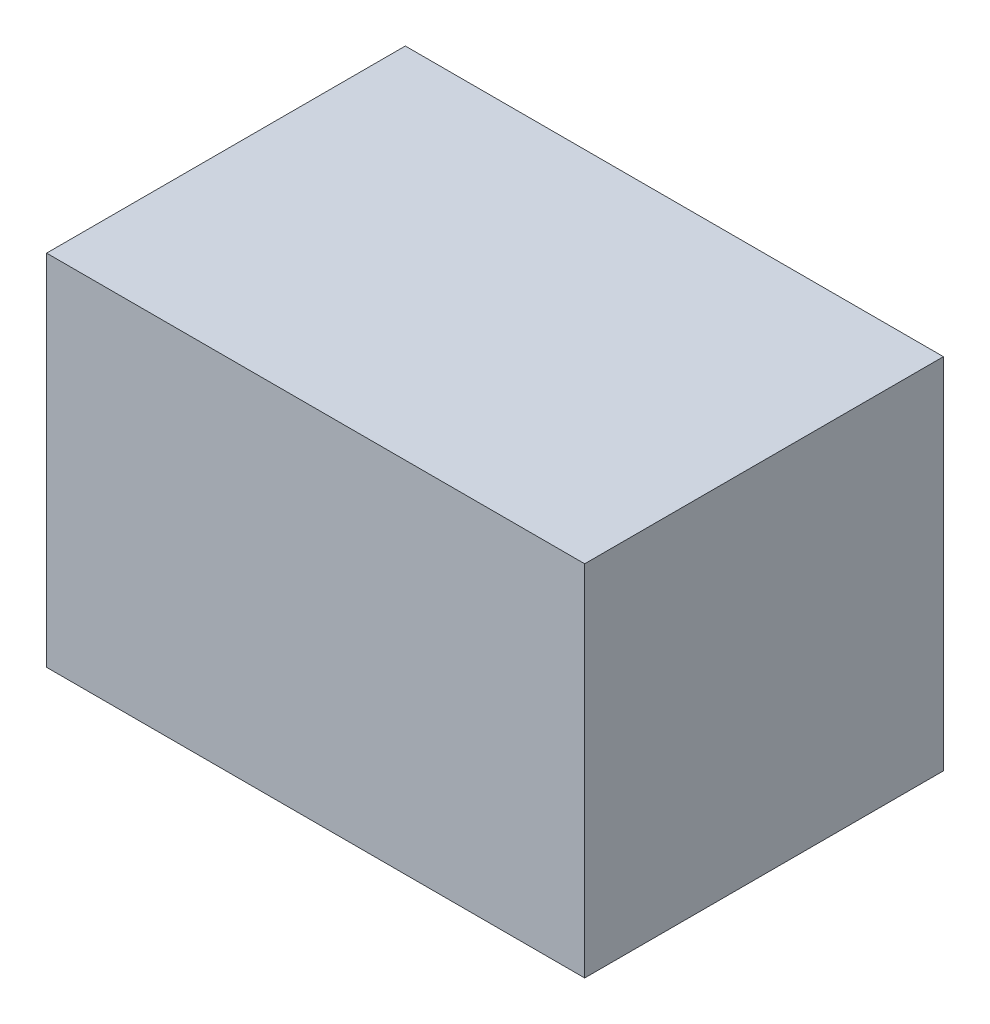
SolidWorks part; units mm, degrees
material "Custom Plastic"
ref_plane "X-Y Datum" through (0, 0, 0) normal (0, 0, 1) x (1, 0, 0)
ref_plane "X-Z Datum" through (0, 0, 0) normal (0, 1, 0) x (1, 0, 0)
ref_plane "Y-Z Datum" through (0, 0, 0) normal (1, 0, 0) x (0, 0, -1)
sketch "Sketch1" plane through (0, 0, 0) normal (1, 0, 0) x (0, 0, -1)
  line L1 (0, 0) -> (38.1, 0)
  line L2 (0, 0) -> (0, 38.1)
  line L3 (0, 38.1) -> (38.1, 38.1)
  line L4 (38.1, 0) -> (38.1, 38.1)
  dimension "D1" = 38.1
  dimension "D2" = 38.1
extrude "Boss-Extrude1" add sketch "Sketch1" along normal blind 57.15
